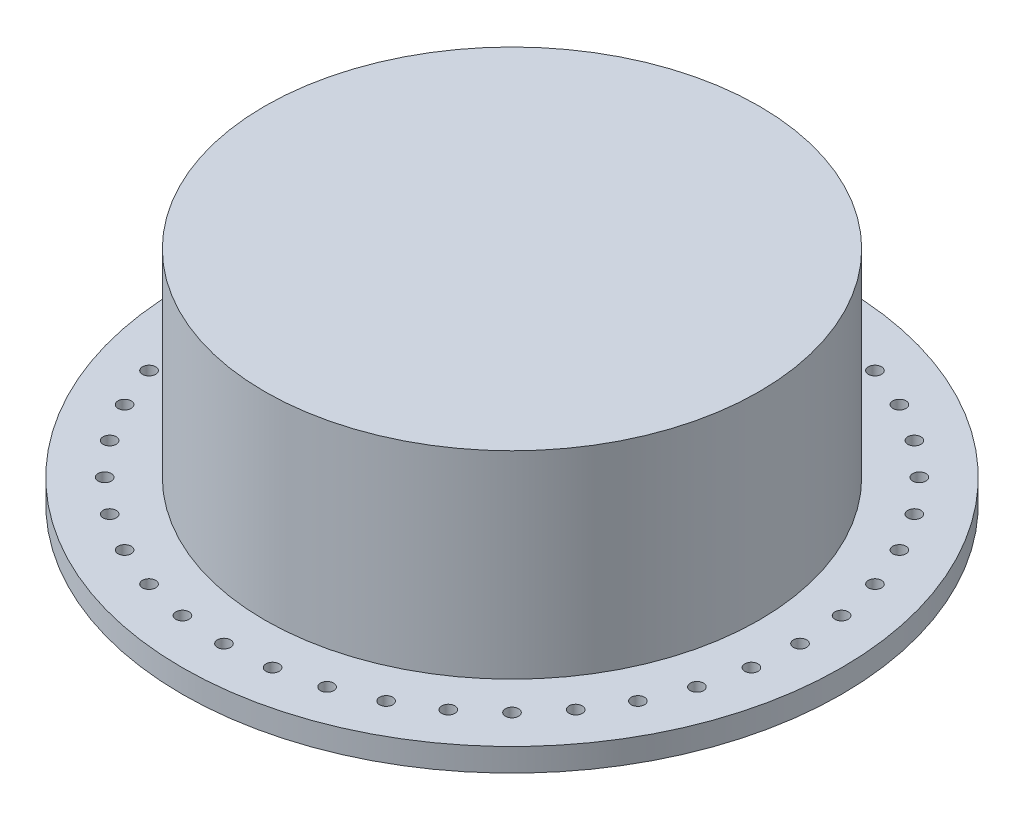
SolidWorks part; units mm, degrees
ref_plane "Ebene vorne" through (0, 0, 0) normal (0, 0, 1) x (1, 0, 0)
ref_plane "Ebene oben" through (0, 0, 0) normal (0, 1, 0) x (1, 0, 0)
ref_plane "Ebene rechts" through (0, 0, 0) normal (1, 0, 0) x (0, 0, -1)
sketch "Skizze1" plane through (0, 0, 0) normal (0, 1, 0) x (1, 0, 0)
  circle A0 centre (0, 0) radius 75
  dimension "D1" = 150
extrude "Aufsatz-Linear austragen1" add sketch "Skizze1" along normal blind 10
sketch "Skizze2" plane through (0, 10, 0) normal (0, 1, 0) x (1, 0, 0)
  circle A0 centre (0, 0) radius 100
  dimension "D1" = 200
extrude "Aufsatz-Linear austragen2" add sketch "Skizze2" along normal blind 7
sketch "Skizze3" plane through (0, 17, 0) normal (0, 1, 0) x (1, 0, 0)
  circle A0 centre (0, 0) radius 75
extrude "Aufsatz-Linear austragen3" add sketch "Skizze3" along normal blind 60
sketch "Skizze4" plane through (0, 17, 0) normal (0, 1, 0) x (1, 0, 0)
  circle A0 centre (0, 87.364) radius 2
  circle A1 centre (13.6667, 86.2884) radius 2
  circle A2 centre (26.9969, 83.0881) radius 2
  circle A3 centre (39.6624, 77.8419) radius 2
  circle A4 centre (51.3512, 70.6789) radius 2
  circle A5 centre (61.7756, 61.7756) radius 2
  circle A6 centre (70.6789, 51.3512) radius 2
  circle A7 centre (77.8419, 39.6624) radius 2
  circle A8 centre (83.0881, 26.9969) radius 2
  circle A9 centre (86.2884, 13.6667) radius 2
  circle A10 centre (87.364, 0) radius 2
  circle A11 centre (86.2884, -13.6667) radius 2
  circle A12 centre (83.0881, -26.9969) radius 2
  circle A13 centre (77.8419, -39.6624) radius 2
  circle A14 centre (70.6789, -51.3512) radius 2
  circle A15 centre (61.7756, -61.7756) radius 2
  circle A16 centre (51.3512, -70.6789) radius 2
  circle A17 centre (39.6624, -77.8419) radius 2
  circle A18 centre (26.9969, -83.0881) radius 2
  circle A19 centre (13.6667, -86.2884) radius 2
  circle A20 centre (0, -87.364) radius 2
  circle A21 centre (-13.6667, -86.2884) radius 2
  circle A22 centre (-26.9969, -83.0881) radius 2
  circle A23 centre (-39.6624, -77.8419) radius 2
  circle A24 centre (-51.3512, -70.6789) radius 2
  circle A25 centre (-61.7756, -61.7756) radius 2
  circle A26 centre (-70.6789, -51.3512) radius 2
  circle A27 centre (-77.8419, -39.6624) radius 2
  circle A28 centre (-83.0881, -26.9969) radius 2
  circle A29 centre (-86.2884, -13.6667) radius 2
  circle A30 centre (-87.364, 0) radius 2
  circle A31 centre (-86.2884, 13.6667) radius 2
  circle A32 centre (-83.0881, 26.9969) radius 2
  circle A33 centre (-77.8419, 39.6624) radius 2
  circle A34 centre (-70.6789, 51.3512) radius 2
  circle A35 centre (-61.7756, 61.7756) radius 2
  circle A36 centre (-51.3512, 70.6789) radius 2
  circle A37 centre (-39.6624, 77.8419) radius 2
  circle A38 centre (-26.9969, 83.0881) radius 2
  circle A39 centre (-13.6667, 86.2884) radius 2
  point P83 (0, 0)
  dimension "D1" = 40
  dimension "D2" = 4
extrude "Schnitt-Linear austragen1" cut sketch "Skizze4" against normal blind 60
